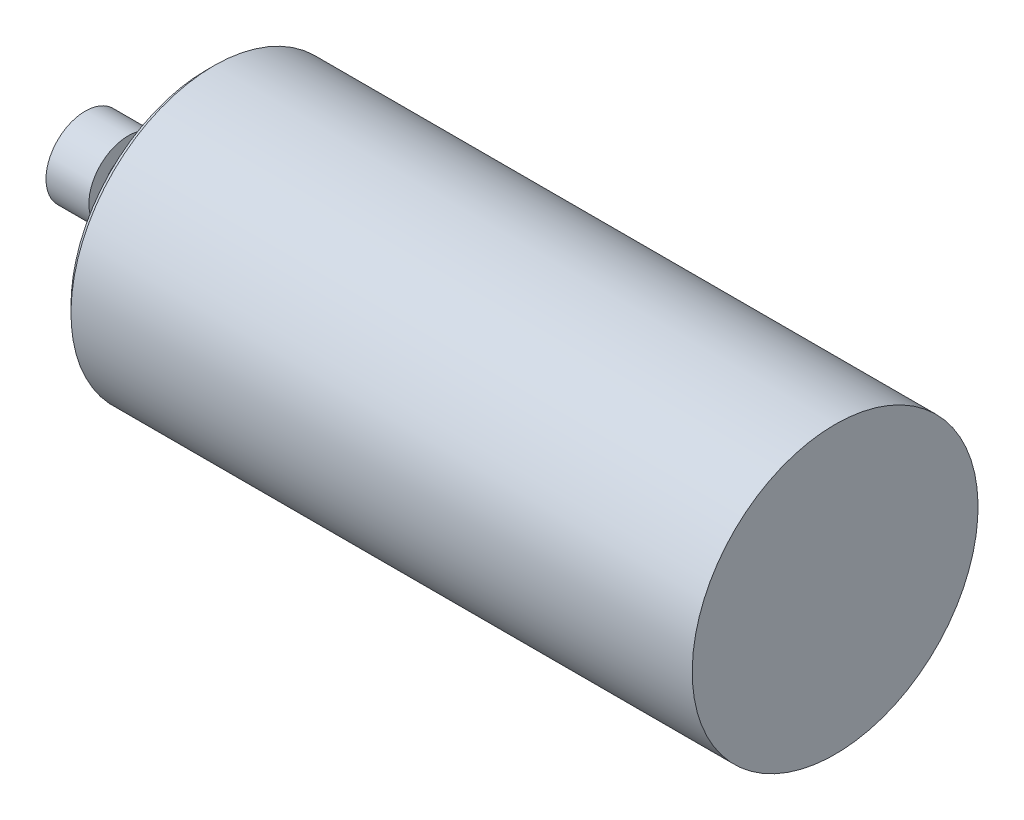
SolidWorks part; units mm, degrees
ref_plane "Plan de face" through (0, 0, 0) normal (0, 0, 1) x (1, 0, 0)
ref_plane "Plan de dessus" through (0, 0, 0) normal (0, 1, 0) x (1, 0, 0)
ref_plane "Plan de droite" through (0, 0, 0) normal (1, 0, 0) x (0, 0, -1)
sketch "Esquisse1" plane through (0, 0, 0) normal (0, 0, 1) x (1, 0, 0)
  line L0 (0, 0) -> (311.4618, 0) construction
  line L1 (278.6359, 0) -> (278.6359, -40)
  line L2 (278.6359, -40) -> (258.7535, -40)
  line L3 (258.7535, -40) -> (104.7535, -40)
  line L4 (104.7535, -38) -> (104.7535, -40)
  line L5 (104.7535, -38) -> (102.7535, -38)
  line L6 (102.7535, -38) -> (98.7535, -38) construction
  line L7 (98.7535, -38) -> (98.7535, -26) construction
  line L8 (98.7535, -26) -> (102.7535, -38)
  line L9 (98.7535, -26) -> (98.7535, -17.5)
  line L10 (98.7535, -17.5) -> (93.7535, -17.5)
  line L11 (93.7535, -17.5) -> (93.7535, -7)
  line L12 (93.7535, -7) -> (80.7535, -7)
  line L13 (80.7535, -7) -> (80.7535, -10.9974)
  line L14 (80.7535, -10.9974) -> (68.7535, -10.9974)
  line L15 (68.7535, -10.9974) -> (68.7535, 0)
  line L16 (278.6359, 0) -> (68.7535, 0)
  dimension "D1" = 2
  dimension "D2" = 4
  dimension "D3" = 12
  dimension "D4" = 154
  dimension "D5" = 19.8824
  dimension "D6" = 40
  dimension "D7" = 8.5
  dimension "D8" = 5
  dimension "D9" = 7
  dimension "D10" = 13
  dimension "D11" = 12
revolve "Révolution1" add sketch "Esquisse1" angle 360 about L16
